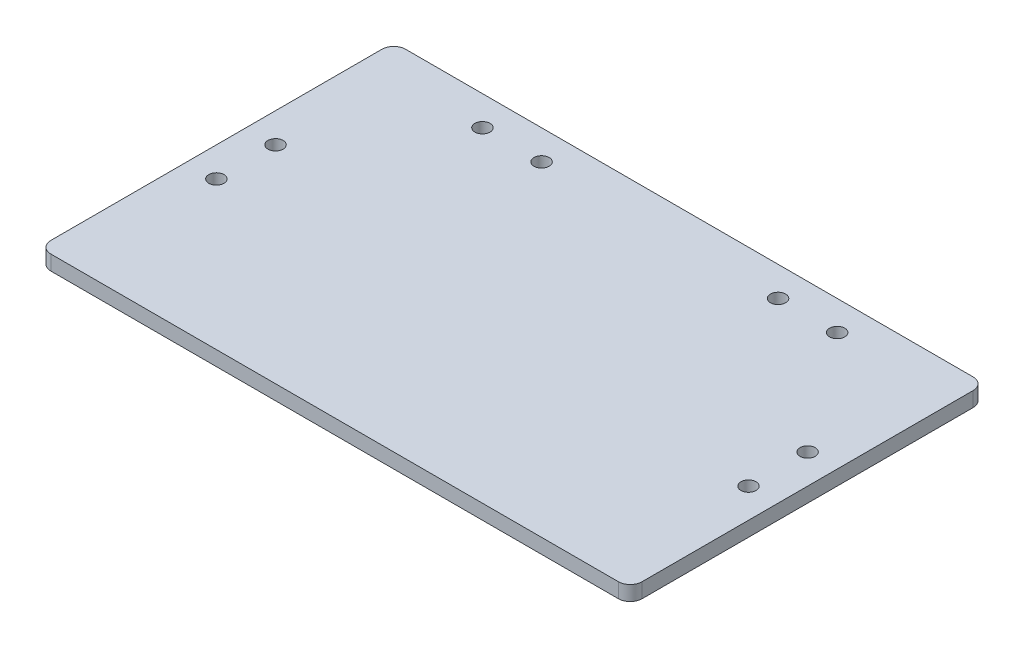
SolidWorks part; units mm, degrees
ref_plane "Front Plane" through (0, 0, 0) normal (0, 0, 1) x (1, 0, 0)
ref_plane "Top Plane" through (0, 0, 0) normal (0, 1, 0) x (1, 0, 0)
ref_plane "Right Plane" through (0, 0, 0) normal (1, 0, 0) x (0, 0, -1)
sketch "Sketch1" plane through (0, 0, 0) normal (0, 1, 0) x (1, 0, 0)
  line L1 (-127, 76.2) -> (127, 76.2)
  line L2 (-127, 76.2) -> (-127, -76.2)
  line L3 (-127, -76.2) -> (127, -76.2)
  line L4 (127, 76.2) -> (127, -76.2)
  line L5 (-127, 76.2) -> (127, -76.2) construction
  line L6 (-127, -76.2) -> (127, 76.2) construction
  point P0 (0, 0)
  dimension "D1" = 152.4
  dimension "D2" = 254
extrude "Boss-Extrude1" add sketch "Sketch1" along normal blind 6.35
sketch "Sketch2" plane through (0, 6.35, 0) normal (0, 1, 0) x (1, 0, 0)
  line L0 (83.82, 43.18) -> (83.82, -65.82) construction
  line L1 (127, -76.2) -> (127, 76.2) construction
  line L2 (127, 76.2) -> (-127, 76.2) construction
  circle A0 centre (83.82, 43.18) radius 2.5
  circle A1 centre (83.82, -65.82) radius 2.5
  dimension "D1" = 5
  dimension "D2" = 109
  dimension "D3" = 43.18
  dimension "D4" = 33.02
extrude "Cut-Extrude1" [suppressed] cut sketch "Sketch2" against normal through all
pattern_linear "LPattern1" [suppressed] count 4 spacing 43.18
sketch "Sketch3" plane through (0, 6.35, 0) normal (0, 1, 0) x (1, 0, 0)
  line L0 (-114.3, 12.7) -> (-114.3, -12.7) construction
  line L1 (-127, 76.2) -> (-127, -76.2) construction
  line L2 (-76.2, 63.5) -> (-50.8, 63.5) construction
  line L3 (127, 76.2) -> (-127, 76.2) construction
  line L4 (0, 0) -> (0, 35.0567) construction
  line L5 (0, 0) -> (31.505, 0) construction
  line L6 (76.2, 63.5) -> (50.8, 63.5) construction
  line L7 (114.3, 12.7) -> (114.3, -12.7) construction
  circle A0 centre (-114.3, 12.7) radius 3.2639
  circle A1 centre (-114.3, -12.7) radius 3.2639
  circle A2 centre (-76.2, 63.5) radius 3.2639
  circle A3 centre (-50.8, 63.5) radius 3.2639
  circle A4 centre (50.8, 63.5) radius 3.2639
  circle A5 centre (76.2, 63.5) radius 3.2639
  circle A6 centre (114.3, -12.7) radius 3.2639
  circle A7 centre (114.3, 12.7) radius 3.2639
  point P16 (-114.3, 0)
  dimension "D1" = 25.4
  dimension "D2" = 6.5278
  dimension "D3" = 12.7
  dimension "D4" = 12.7
  dimension "D5" = 101.6
extrude "Cut-Extrude2" cut sketch "Sketch3" against normal through all
sketch "Sketch4" [suppressed] plane through (0, 6.35, 0) normal (0, 1, 0) x (1, 0, 0)
  line L2 (-127, -76.2) -> (127, -76.2) construction
  line L3 (-91.44, -55.88) -> (-86.36, -55.88)
  line L4 (-91.44, -55.88) -> (-91.44, -45.72)
  line L5 (-91.44, -45.72) -> (-86.36, -45.72)
  line L6 (-86.36, -55.88) -> (-86.36, -45.72)
  line L7 (-91.44, -55.88) -> (-86.36, -45.72) construction
  line L8 (-91.44, -45.72) -> (-86.36, -55.88) construction
  line L10 (-127, 76.2) -> (-127, -76.2) construction
  point P0 (-88.9, -50.8)
  dimension "D1" = 25.4
  dimension "D3" = 10.16
  dimension "D2" = 38.1
  dimension "D4" = 5.08
extrude "Cut-Extrude3" [suppressed] cut sketch "Sketch4" against normal through all
fillet "Fillet1" radius 5.08 4 edges at (-127, 3.175, 76.2) (127, 3.175, 76.2) (127, 3.175, -76.2) (-127, 3.175, -76.2)
